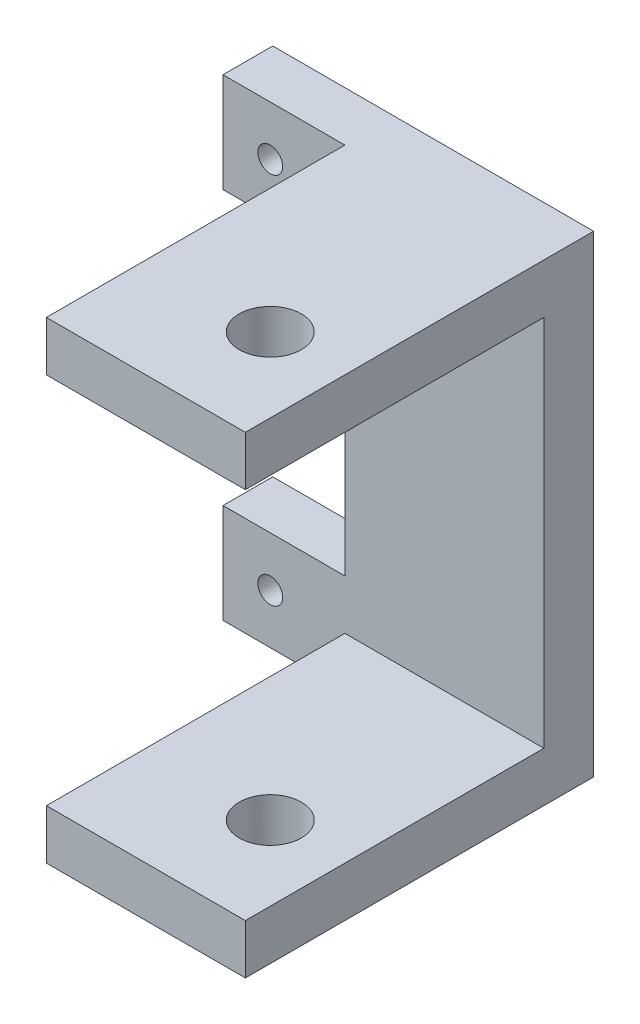
SolidWorks part; units mm, degrees
ref_plane "前视基准面" through (0, 0, 0) normal (0, 0, 1) x (1, 0, 0)
ref_plane "上视基准面" through (0, 0, 0) normal (0, 1, 0) x (1, 0, 0)
ref_plane "右视基准面" through (0, 0, 0) normal (1, 0, 0) x (0, 0, -1)
sketch "草图2" plane through (0, 0, 0) normal (0, 0, 1) x (1, 0, 0)
  line L3 (-4.9, -9.5) -> (8, -9.5)
  line L4 (8, 9.5) -> (8, -9.5)
  line L5 (0, 0) -> (2.4933, 0) construction
  line L6 (0, 0) -> (0, -3.9686) construction
  line L15 (-4.9, 9.5) -> (8, 9.5)
  line L20 (-4.9, 9.5) -> (-4.9, 5.5)
  line L21 (-4.9, 5.5) -> (0, 5.5)
  line L26 (0, 5.5) -> (0, -5.5)
  line L28 (-4.9, -5.5) -> (0, -5.5)
  line L29 (-4.9, -5.5) -> (-4.9, -9.5)
  point P0 (0, 0)
  dimension "D1" = 4.9
  dimension "D2" = 8
  dimension "D3" = 19
  dimension "D4" = 4
  dimension "D5" = 4
extrude "凸台-拉伸1" add sketch "草图2" along normal blind 2
sketch "草图3" plane through (0, 0, 2) normal (0, 0, 1) x (1, 0, 0)
  line L1 (0, 9.5) -> (8, 9.5)
  line L2 (0, 9.5) -> (0, 7.5)
  line L3 (0, 7.5) -> (8, 7.5)
  line L4 (8, 9.5) -> (8, 7.5)
  line L5 (8, -9.5) -> (8, 9.5) construction
  line L6 (0, -7.5) -> (8, -7.5)
  line L8 (0, -9.5) -> (8, -9.5)
  line L9 (8, -7.5) -> (8, -9.5)
  line L10 (-4.9, -9.5) -> (8, -9.5) construction
  line L11 (0, -7.5) -> (0, -9.5)
  line L12 (8, 9.5) -> (-4.9, 9.5) construction
  dimension "D1" = 2
  dimension "D2" = 2
  dimension "D3" = 8
  dimension "D4" = 8
extrude "凸台-拉伸2" add sketch "草图3" along normal blind 12
sketch "草图10" plane through (0, 0, 2) normal (0, 0, 1) x (1, 0, 0)
  line L6 (-4.9, 9.5) -> (-4.9, 5.5) construction
  line L7 (0, 9.5) -> (-4.9, 9.5) construction
  line L8 (0, 0) -> (-11.8404, 0) construction
  circle A0 centre (-3, 7.5) radius 0.5
  circle A1 centre (-3, -7.5) radius 0.5
  point P4 (0, 0)
  dimension "D3" = 1
  dimension "D4" = 1
  dimension "D1" = 1.9
  dimension "D2" = 2
sketch "草图11" plane through (0, -9.5, 0) normal (0, -1, 0) x (1, 0, 0)
  line L0 (0, 14) -> (0, 2) construction
  line L3 (-4.9, 0) -> (8, 0) construction
  circle A0 centre (5, 10) radius 1.25
  dimension "D1" = 2.5
  dimension "D2" = 5
  dimension "D3" = 10
extrude "切除-拉伸3" cut sketch "草图11" against normal through all
extrude "切除-拉伸4" cut sketch "草图10" against normal up to next
